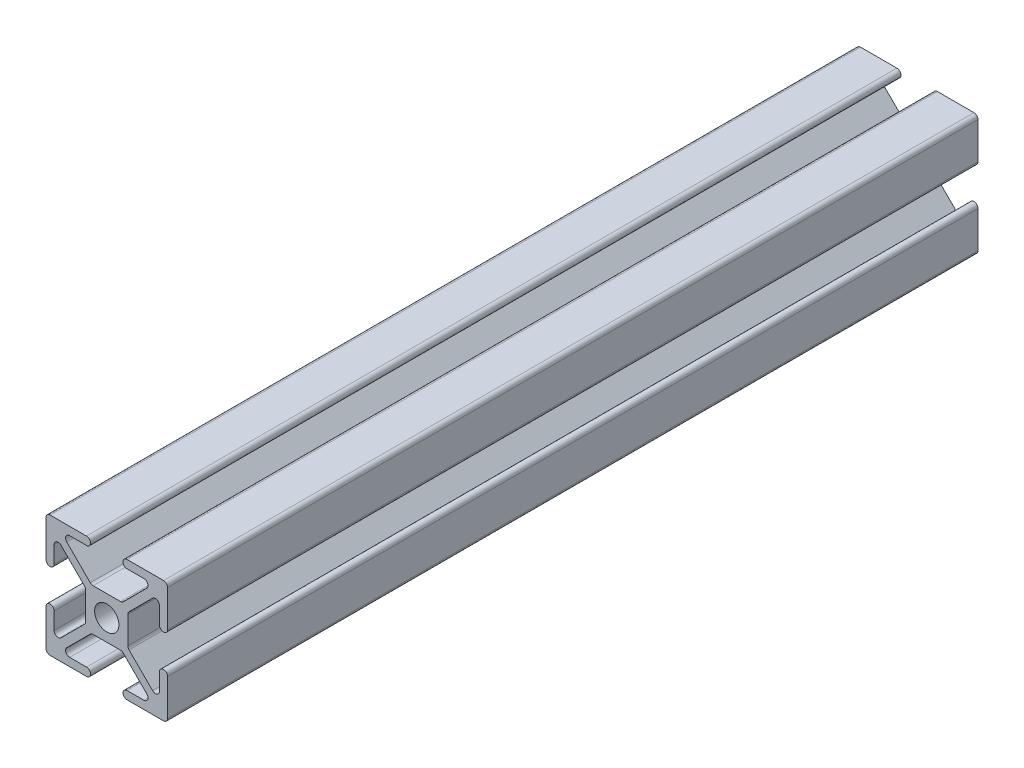
SolidWorks part; units mm, degrees
ref_plane "Alzado" through (0, 0, 0) normal (0, 0, 1) x (1, 0, 0)
ref_plane "Planta" through (0, 0, 0) normal (0, 1, 0) x (1, 0, 0)
ref_plane "Vista lateral" through (0, 0, 0) normal (1, 0, 0) x (0, 0, -1)
sketch "Croquis1" plane through (0, 0, 0) normal (0, 0, 1) x (1, 0, 0)
  line L1 (-14, 15) -> (14, 15)
  line L2 (-15, 14) -> (-15, -14)
  line L3 (-14, -15) -> (14, -15)
  line L4 (15, 14) -> (15, -14)
  line L5 (-15, 15) -> (15, -15) construction
  line L6 (-15, -15) -> (15, 15) construction
  arc A0 (-14, 15) -> (-15, 14) centre (-14, 14) ccw
  arc A1 (14, -15) -> (15, -14) centre (14, -14) ccw
  arc A2 (-14, -15) -> (-15, -14) centre (-14, -14) cw
  arc A3 (15, 14) -> (14, 15) centre (14, 14) ccw
  point P0 (0, 0)
  dimension "D3" = 1
  dimension "D4" = 1
  dimension "D1" = 30
  dimension "D2" = 30
extrude "Saliente-Extruir1" add sketch "Croquis1" against normal blind 200
sketch "Croquis2" plane through (0, 0, 0) normal (0, 0, 1) x (1, 0, 0)
  circle A0 centre (0, 0) radius 3
  dimension "D1" = 6
sketch "Croquis3" plane through (0, 0, 0) normal (0, 0, 1) x (1, 0, 0)
  line L0 (-15, 0) -> (15, 0) construction
  line L1 (4.0787, -5.4929) -> (9.8787, -11.2929)
  line L2 (-11.2929, 9.8787) -> (-5.4929, 4.0787)
  line L3 (-9.8787, 11.2929) -> (-4.0787, 5.4929)
  line L4 (-13, 9.1716) -> (-13, 5)
  line L5 (-15, 14) -> (-15, -14) construction
  line L6 (-5.2, 3.3716) -> (-5.2, -3.3716)
  line L7 (-9.1716, 13) -> (-5, 13)
  line L8 (9.8787, 11.2929) -> (4.0787, 5.4929)
  line L9 (11.2929, 9.8787) -> (5.4929, 4.0787)
  line L10 (-3.3716, 5.2) -> (3.3716, 5.2)
  line L11 (14, 15) -> (-14, 15) construction
  line L12 (13, 9.1716) -> (13, 5)
  line L13 (5.2, 3.3716) -> (5.2, -3.3716)
  line L14 (15, -14) -> (15, 14) construction
  line L15 (-9.1716, -13) -> (-5, -13)
  line L16 (-3.3716, -5.2) -> (3.3716, -5.2)
  line L17 (-14, -15) -> (14, -15) construction
  line L18 (-5.4929, -4.0787) -> (-11.2929, -9.8787)
  line L19 (5.4929, -4.0787) -> (11.2929, -9.8787)
  line L20 (-4.0787, -5.4929) -> (-9.8787, -11.2929)
  line L21 (5, -13) -> (9.1716, -13)
  line L22 (-13, -5) -> (-13, -9.1716)
  line L23 (13, -5) -> (13, -9.1716)
  line L24 (0, 15) -> (0, -5.2) construction
  line L34 (5, 13) -> (9.1716, 13)
  arc A0 (9.8787, 11.2929) -> (9.1716, 13) centre (9.1716, 12) ccw
  arc A1 (-9.8787, 11.2929) -> (-9.1716, 13) centre (-9.1716, 12) cw
  arc A2 (9.8787, 11.2929) -> (9.1716, 13) centre (9.1716, 12) ccw
  arc A3 (13, 9.1716) -> (11.2929, 9.8787) centre (12, 9.1716) ccw
  arc A4 (11.2929, -9.8787) -> (13, -9.1716) centre (12, -9.1716) ccw
  arc A5 (9.1716, -13) -> (9.8787, -11.2929) centre (9.1716, -12) ccw
  arc A6 (-9.1716, -13) -> (-9.8787, -11.2929) centre (-9.1716, -12) cw
  arc A7 (-11.2929, -9.8787) -> (-13, -9.1716) centre (-12, -9.1716) cw
  arc A8 (-13, 9.1716) -> (-11.2929, 9.8787) centre (-12, 9.1716) cw
  arc A9 (-4.0787, -5.4929) -> (-3.3716, -5.2) centre (-3.3716, -6.2) cw
  arc A10 (3.3716, -5.2) -> (4.0787, -5.4929) centre (3.3716, -6.2) cw
  arc A11 (5.4929, -4.0787) -> (5.2, -3.3716) centre (6.2, -3.3716) cw
  arc A12 (5.2, 3.3716) -> (5.4929, 4.0787) centre (6.2, 3.3716) cw
  arc A13 (3.3716, 5.2) -> (4.0787, 5.4929) centre (3.3716, 6.2) ccw
  arc A14 (-3.3716, 5.2) -> (-4.0787, 5.4929) centre (-3.3716, 6.2) cw
  arc A15 (-5.4929, -4.0787) -> (-5.2, -3.3716) centre (-6.2, -3.3716) ccw
  arc A16 (-5.2, 3.3716) -> (-5.4929, 4.0787) centre (-6.2, 3.3716) ccw
  circle A17 centre (-14, -5) radius 1
  circle A18 centre (-14, 5) radius 1
  circle A19 centre (-5, -14) radius 1
  circle A20 centre (5, -14) radius 1
  circle A21 centre (14, 5) radius 1
  circle A22 centre (14, -5) radius 1
  circle A23 centre (-5, 14) radius 1
  circle A24 centre (5, 14) radius 1
  point P20 (-11.5858, -13)
  point P30 (-13, -11.5858)
  point P43 (-3.7858, -5.2)
  point P50 (3.7858, -5.2)
  point P53 (5.2, -3.7858)
  point P62 (-5.2, -3.7858)
  line M2 (-15, 14) -> (-15, -14)
  line M4 (-14, -15) -> (14, -15)
  line M6 (15, -14) -> (15, 14)
  line M8 (14, 15) -> (-14, 15)
  dimension "D6" = 9.8
  dimension "D7" = 2
  dimension "D12" = 2
  dimension "D19" = 1
  dimension "D2" = 1
  dimension "D3" = 1
  dimension "D4" = 1
  dimension "D16" = 1
  dimension "D5" = 2
  dimension "D8" = 9.8
  dimension "D9" = 2
  dimension "D10" = 9.8
  dimension "D11" = 9.8
  dimension "D15" = 1
  dimension "D20" = 1
  dimension "D23" = 1
  dimension "D24" = 1
  dimension "D27" = 1
  dimension "D28" = 1
extrude "Cortar-Extruir1" cut sketch "Croquis2" against normal through all
extrude "Cortar-Extruir3" cut sketch "Croquis3" against normal through all contours A18 A17 L22 A7 L18 A15 L6 A16 L2 A8 L4 M2 | A24 A23 L7 A1 L3 A14 L10 A13 L8 A0 L34 M8 | A20 L21 A5 L1 A10 L16 A9 L20 A6 L15 A19 M4 | A22 A21 L12 A3 L9 A12 L13 A11 L19 A4 L23 M6
